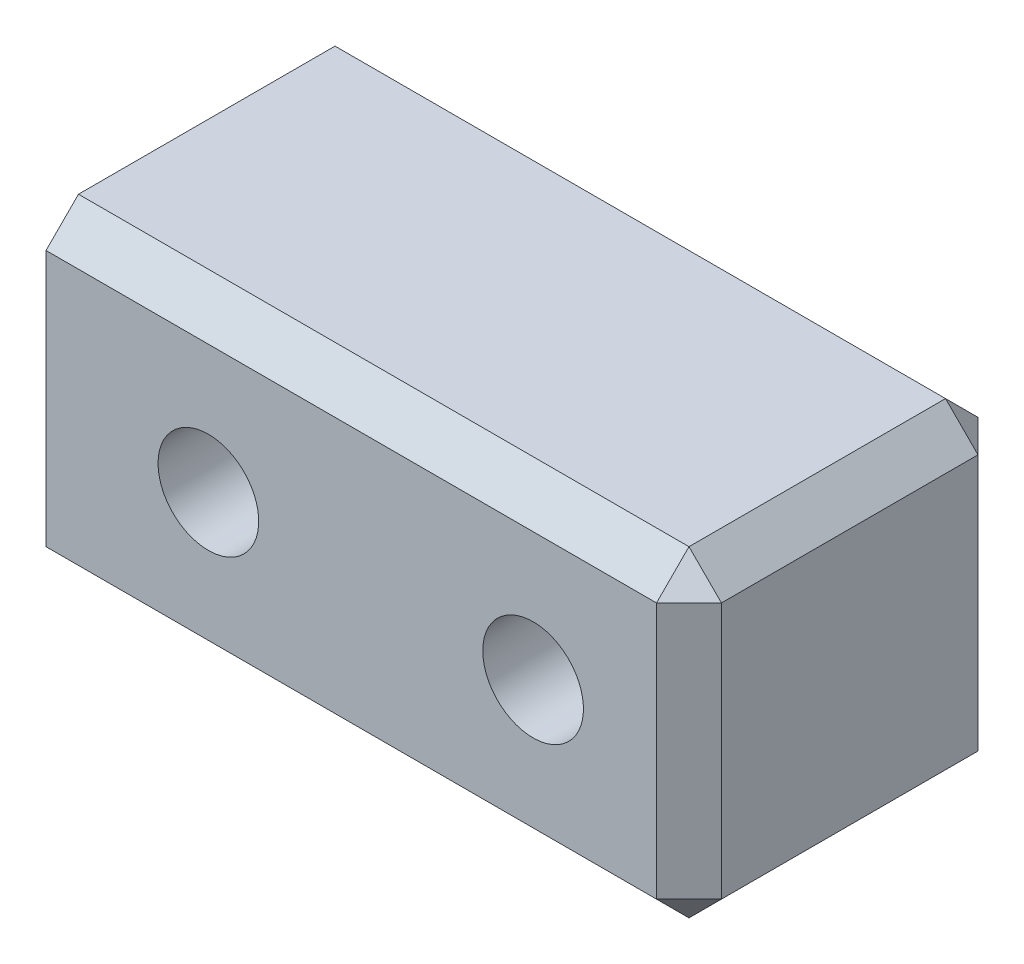
SolidWorks part; units mm, degrees
ref_plane "前视基准面" through (0, 0, 0) normal (0, 0, 1) x (1, 0, 0)
ref_plane "上视基准面" through (0, 0, 0) normal (0, 1, 0) x (1, 0, 0)
ref_plane "右视基准面" through (0, 0, 0) normal (1, 0, 0) x (0, 0, -1)
other "Configuration Table"
sketch "草图1" plane through (0, 0, 0) normal (0, 0, 1) x (1, 0, 0)
  line L0 (0, 4.95) -> (19.8, 4.95) construction
  line L1 (0, 0) -> (19.8, 0)
  line L2 (0, 0) -> (0, 9.9)
  line L3 (0, 9.9) -> (19.8, 9.9)
  line L4 (19.8, 0) -> (19.8, 9.9)
  circle A0 centre (5, 4.95) radius 1.55
  circle A1 centre (15, 4.95) radius 1.55
  dimension "D3" = 3.1
  dimension "D4" = 3.1
  dimension "D1" = 19.8
  dimension "D2" = 9.9
  dimension "D5" = 5
  dimension "D6" = 10
extrude "凸台-拉伸1" add sketch "草图1" along normal blind 9.9
chamfer "倒角1" distance 1 angle 45 12 edges at (19.8, 0, 4.95) (19.8, 4.95, 9.9) (19.8, 9.9, 4.95) (19.8, 4.95, 0) (0, 9.9, 4.95) (9.9, 9.9, 0) (0, 4.95, 0) (9.9, 0, 0) (0, 0, 4.95) (9.9, 0, 9.9) (0, 4.95, 9.9) (9.9, 9.9, 9.9)
